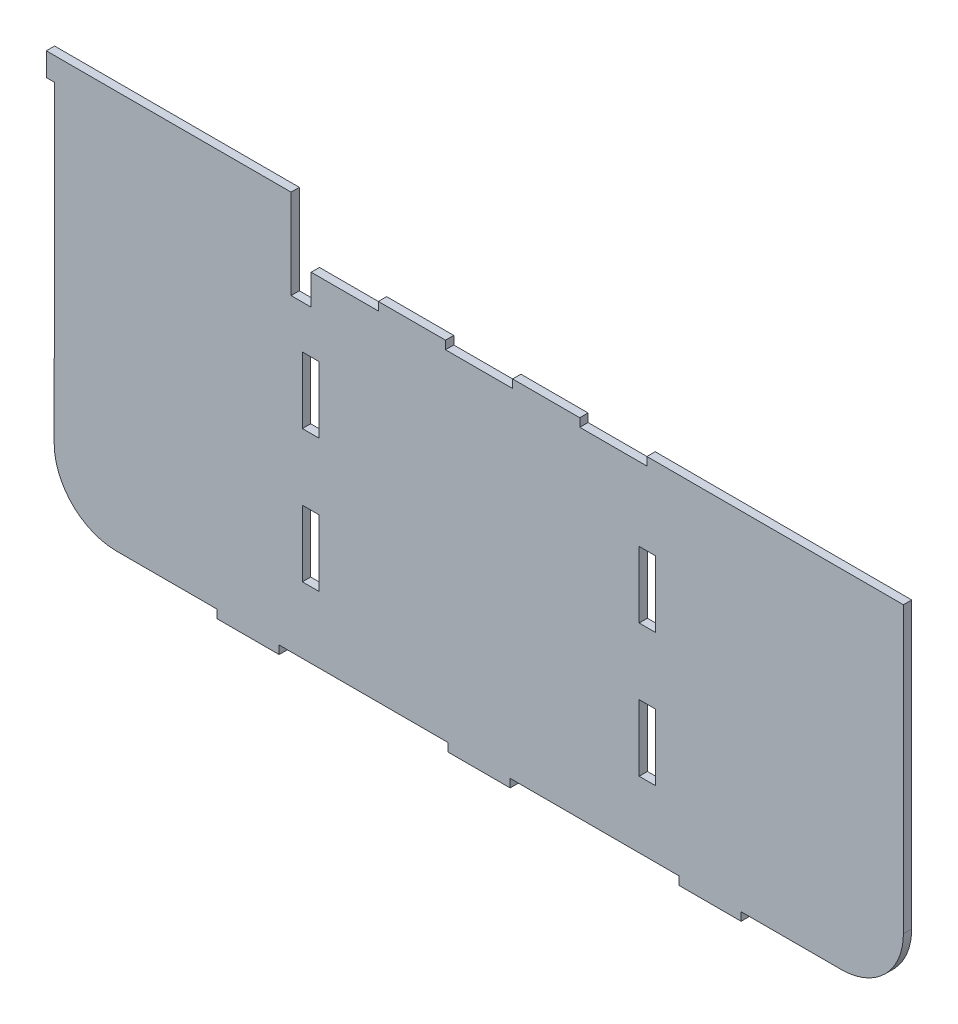
SolidWorks part; units mm, degrees
ref_plane "Front Plane" through (0, 0, 0) normal (0, 0, 1) x (1, 0, 0)
ref_plane "Top Plane" through (0, 0, 0) normal (0, 1, 0) x (1, 0, 0)
ref_plane "Right Plane" through (0, 0, 0) normal (1, 0, 0) x (0, 0, -1)
sketch "Sketch1" plane through (0, 0, 0) normal (0, 0, 1) x (1, 0, 0)
  line L12 (-444.5, 10.16) -> (-321.2, 10.16)
  line L16 (-245, 10.16) -> (-38.1, 10.16)
  line L20 (38.1, 10.16) -> (245, 10.16)
  line L27 (205.7064, 435.61) -> (205.558, 425.45)
  line L28 (205.558, 425.45) -> (123.444, 425.45)
  line L29 (123.444, 425.45) -> (123.444, 435.61)
  line L30 (123.444, 435.61) -> (41.148, 435.61)
  line L31 (41.148, 435.61) -> (41.148, 425.45)
  line L32 (41.148, 425.45) -> (-41.148, 425.45)
  line L33 (-41.148, 425.45) -> (-41.148, 435.61)
  line L34 (-41.148, 435.61) -> (-123.444, 435.61)
  line L35 (-123.444, 435.61) -> (-123.444, 425.45)
  line L36 (-123.444, 425.45) -> (-205.74, 425.45)
  line L37 (-205.74, 425.45) -> (-205.74, 388.35)
  line L38 (-205.74, 388.35) -> (-230.3597, 388.35)
  line L39 (-520.3601, 435.61) -> (-520.7, 86.36)
  line L43 (-38.1, 10.16) -> (-38.1, 0) construction
  line L45 (38.1, 10.16) -> (38.1, 0) construction
  line L46 (38.1, 10.16) -> (38.1, 0)
  line L47 (-38.1, 10.16) -> (-38.1, 0)
  line L48 (245, 10.16) -> (245, 0) construction
  line L49 (321.2, 10.16) -> (321.2, 0) construction
  line L50 (245, 10.16) -> (245, 0)
  line L51 (321.2, 10.16) -> (321.2, 0)
  line L52 (-245, 10.16) -> (-245, 0) construction
  line L53 (-321.2, 10.16) -> (-321.2, 0) construction
  line L54 (-321.2, 10.16) -> (-321.2, 0)
  line L55 (-245, 10.16) -> (-245, 0)
  line L56 (216.5353, 172.7939) -> (216.5353, 91.4769) construction
  line L57 (216.5353, 335.4278) -> (216.5353, 254.1108) construction
  line L58 (216.5353, 172.7939) -> (216.5353, 91.4769)
  line L59 (216.5353, 335.4278) -> (216.5353, 254.1108)
  line L62 (-216.5353, 172.7939) -> (-216.5353, 91.4769)
  line L63 (-216.5353, 335.4278) -> (-216.5353, 254.1108)
  line L64 (196.2153, 335.4278) -> (196.2153, 254.1108)
  line L65 (-196.2153, 335.4278) -> (-196.2153, 254.1108)
  line L66 (-196.2153, 172.7939) -> (-196.2153, 91.4769)
  line L67 (196.2153, 172.7939) -> (196.2153, 91.4769)
  line L68 (196.2153, 335.4278) -> (216.5353, 335.4278)
  line L69 (-196.2153, 335.4278) -> (-216.5353, 335.4278)
  line L70 (-216.5353, 254.1108) -> (-196.2153, 254.1108)
  line L71 (-196.2153, 172.7939) -> (-216.5353, 172.7939)
  line L72 (-196.2153, 91.4769) -> (-216.5353, 91.4769)
  line L73 (196.2153, 91.4769) -> (216.5353, 91.4769)
  line L74 (216.5353, 172.7939) -> (196.2153, 172.7939)
  line L75 (216.5353, 254.1108) -> (196.2153, 254.1108)
  line L76 (-520.3601, 435.61) -> (-520.3601, 469.7464)
  line L77 (-520.3601, 469.7464) -> (-530.3597, 469.6549)
  line L78 (-530.3597, 469.6549) -> (-530.3597, 498.1549)
  line L79 (-530.3597, 498.1549) -> (-230.3597, 498.1549)
  line L81 (321.2, 0) -> (245, 0)
  line L82 (38.1, 0) -> (-38.1, 0)
  line L83 (-245, 0) -> (-321.2, 0)
  line L84 (-230.3597, 498.1549) -> (-230.3597, 388.35)
  line L85 (520.0465, 86.2) -> (520.0703, 435.45) construction
  line L86 (520.0465, 86.2) -> (520.0703, 435.45)
  line L87 (444.5, 10.16) -> (321.2, 10.16)
  line L88 (-520.3601, 435.61) -> (580.4446, 435.61) construction
  line L89 (-123.444, 425.45) -> (629.1878, 425.45) construction
  line L90 (205.7064, 435.61) -> (520.0703, 435.45)
  arc A0 (-520.7, 86.36) -> (-444.5, 10.16) centre (-444.5, 86.36) ccw
  ellipse E3 centre (443.8465, 86.3572) end of major axis (520.0467, 86.3572) minor radius 76.2 (444.5, 10.16) -> (520.0465, 86.2) ccw
  dimension "D2" = 20.32
  dimension "D1" = 28.5
  dimension "D4" = 20.32
  dimension "D5" = 20.32
  dimension "D6" = 20.32
  dimension "D7" = 300
other "AlignGroup1"
extrude "Boss-Extrude1" add sketch "Sketch1" along normal blind 10.16
